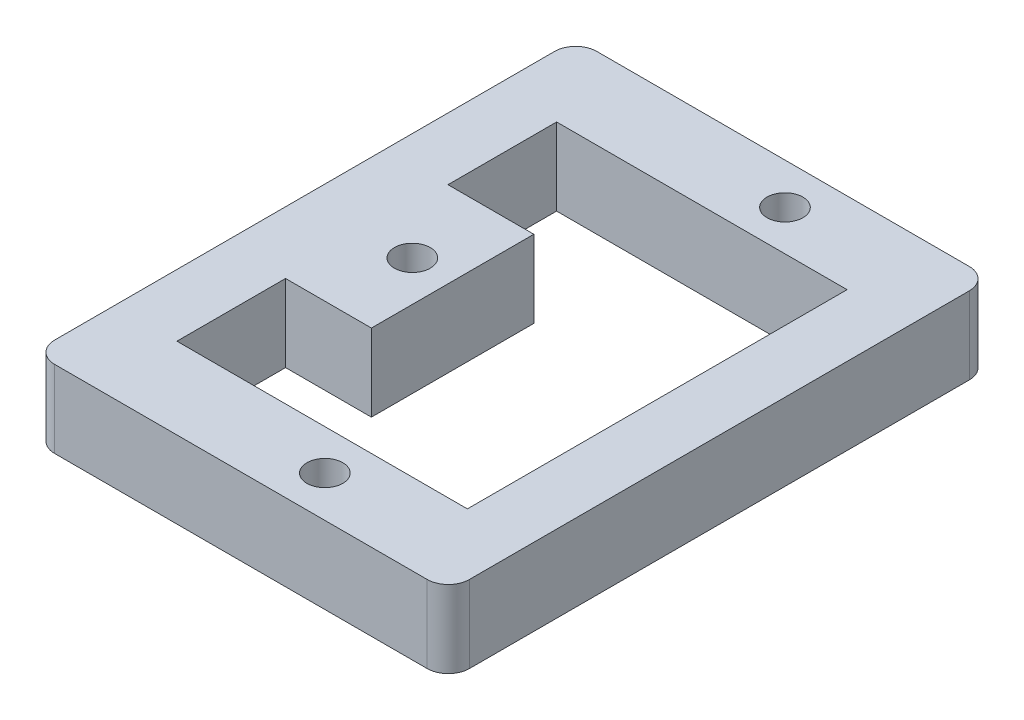
SolidWorks part; units mm, degrees
material "Custom Plastic"
ref_plane "Front Plane" through (0, 0, 0) normal (0, 0, 1) x (1, 0, 0)
ref_plane "Top Plane" through (0, 0, 0) normal (0, 1, 0) x (1, 0, 0)
ref_plane "Right Plane" through (0, 0, 0) normal (1, 0, 0) x (0, 0, -1)
sketch "Sketch1" plane through (0, 0, 0) normal (0, 1, 0) x (1, 0, 0)
  line L0 (8.7437, 11.43) -> (8.7437, -11.43)
  line L1 (-12.4841, -16.3195) -> (12.4841, -16.3195)
  line L2 (-12.4841, -16.3195) -> (-12.4841, 16.3195)
  line L3 (-12.4841, 16.3195) -> (12.4841, 16.3195)
  line L4 (12.4841, -16.3195) -> (12.4841, 16.3195)
  line L5 (-12.4841, -16.3195) -> (12.4841, 16.3195) construction
  line L6 (-12.4841, 16.3195) -> (12.4841, -16.3195) construction
  line L7 (8.7437, -11.43) -> (-8.7437, -11.43)
  line L8 (-8.7437, -11.43) -> (-8.7437, -4.8895)
  line L9 (-8.7437, -4.8895) -> (-3.5753, -4.8895)
  line L10 (-3.5753, -4.8895) -> (-3.5753, 4.8895)
  line L11 (-3.5753, 4.8895) -> (-8.7437, 4.8895)
  line L12 (-8.7437, 4.8895) -> (-8.7437, 11.43)
  line L13 (-8.7437, 11.43) -> (8.7437, 11.43)
  point P0 (0, 0)
  point P8 (8.6964, 11.9681)
  point P15 (-6.8245, -4.2698)
  point P16 (-5.9828, -2.3501)
  point P17 (9.222, 12.0552)
  dimension "D1" = 32.639
  dimension "D2" = 24.9682
  dimension "D3" = 12.319
  dimension "D4" = 9.779
  dimension "D5" = 22.86
extrude "Boss-Extrude1" add sketch "Sketch1" along normal blind 4.6482 contours L13 L12 L11 L10 L9 L8 L7 L0 | L3 L4 L1 L2
sketch "Sketch2" plane through (0, 4.6482, 0) normal (0, 1, 0) x (1, 0, 0)
  line L0 (-3.5753, 0) -> (8.7437, 0) construction
  line L1 (-3.5753, -4.8895) -> (-3.5753, 4.8895) construction
  line L2 (8.7437, 11.43) -> (8.7437, -11.43) construction
  line L3 (2.5842, 0) -> (2.5842, 13.8506) construction
  line L4 (2.5842, 0) -> (2.5842, -13.8506) construction
  line L5 (-3.5753, 0) -> (-4.9215, 0) construction
  line L6 (-4.9215, 0) -> (-6.001, 0) construction
  circle A0 centre (2.5842, 13.8506) radius 1.0795
  circle A1 centre (2.5842, -13.8506) radius 1.0795
  circle A2 centre (-6.001, 0) radius 1.0795
  dimension "D2" = 2.159
  dimension "D1" = 27.7012
  dimension "D3" = 1.3462
extrude "Cut-Extrude1" cut sketch "Sketch2" against normal blind 4.6482
fillet "Fillet1" radius 1.27 4 edges at (-12.4841, 2.3241, 16.3195) (12.4841, 2.3241, 16.3195) (12.4841, 2.3241, -16.3195) (-12.4841, 2.3241, -16.3195)
